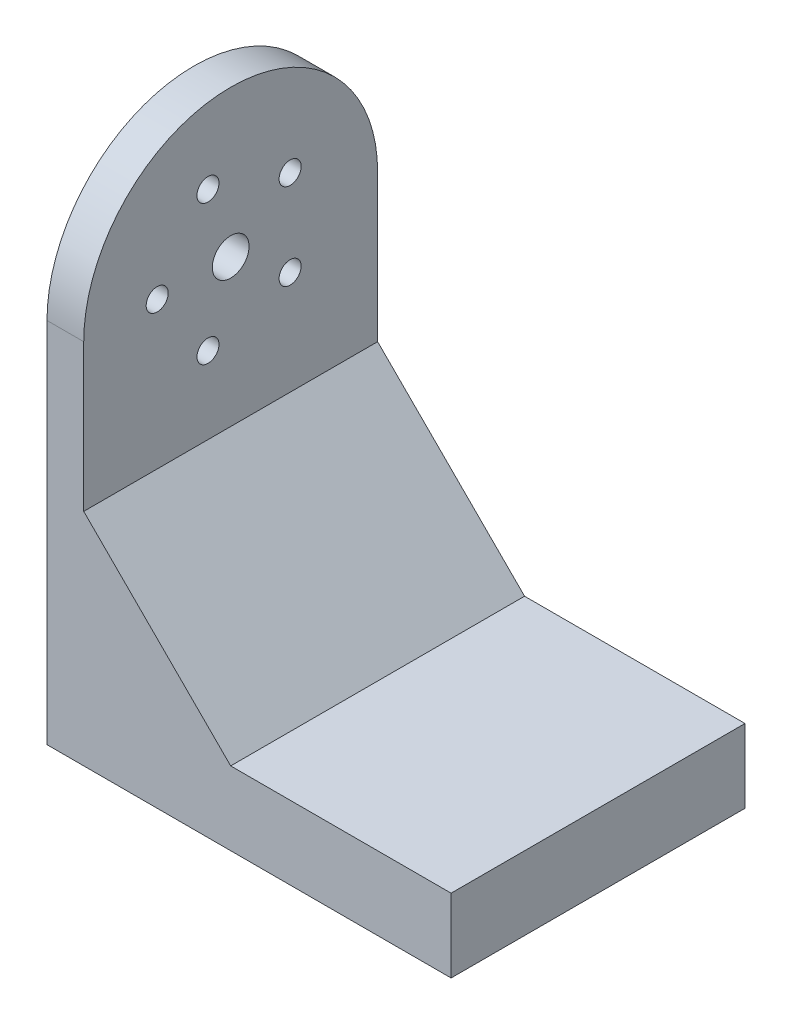
SolidWorks part; units mm, degrees
ref_plane "Front Plane" through (0, 0, 0) normal (0, 0, 1) x (1, 0, 0)
ref_plane "Top Plane" through (0, 0, 0) normal (0, 1, 0) x (1, 0, 0)
ref_plane "Right Plane" through (0, 0, 0) normal (1, 0, 0) x (0, 0, -1)
sketch "Sketch1" plane through (0, 0, 0) normal (1, 0, 0) x (0, 0, -1)
  line L1 (-20, -50) -> (20, -50)
  line L2 (-20, -50) -> (-20, 0)
  line L3 (-20, 0) -> (20, 0)
  line L4 (20, -50) -> (20, 0)
  circle A0 centre (0, 0) radius 20
  circle A1 centre (0, 0) radius 10 construction
  circle A2 centre (-10, 0) radius 1.5
  circle A7 centre (-3.0902, 9.5106) radius 1.5
  circle A8 centre (8.0902, 5.8779) radius 1.5
  circle A9 centre (8.0902, -5.8779) radius 1.5
  circle A10 centre (-3.0902, -9.5106) radius 1.5
  circle A11 centre (0, 0) radius 2.5
  point P16 (-2.5, -3.441)
  point P17 (0, 0)
  dimension "D1" = 20
  dimension "D2" = 3
  dimension "D4" = 40
  dimension "D5" = 50
  dimension "D3" = 5
extrude "Boss-Extrude11" add sketch "Sketch1" along normal blind 5 contours A0 L2 L1 L4 | A2 L3 A0 A10 A9 | A2 L3 A0 A8 A7
sketch "Sketch2" plane through (5, 0, 0) normal (1, 0, 0) x (0, 0, -1)
  line L0 (-20, -50) -> (-20, 0) construction
  line L1 (20, -50) -> (-20, -50)
  line L2 (20, -50) -> (20, -40)
  line L3 (20, -40) -> (-20, -40)
  line L4 (-20, -50) -> (-20, -40)
  point P4 (0, 0)
extrude "Boss-Extrude12" add sketch "Sketch2" along normal blind 50
chamfer "Chamfer1" distance 20 angle 45 1 edges at (5, -40, 0)
